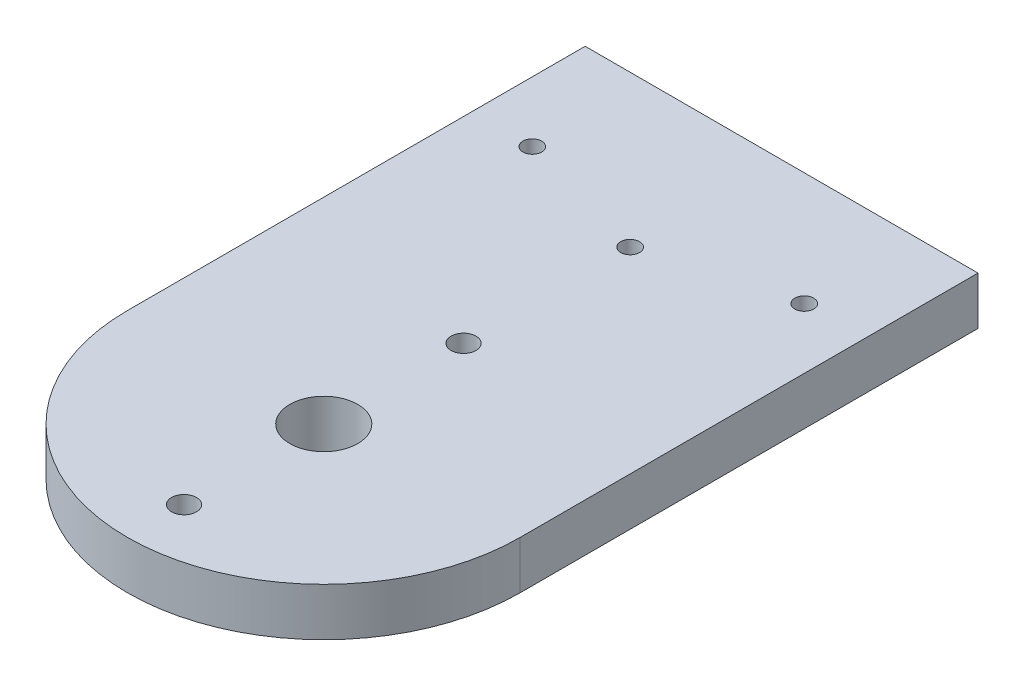
SolidWorks part; units mm, degrees
material "Aleación 6061"
ref_plane "Alzado" through (0, 0, 0) normal (0, 0, 1) x (1, 0, 0)
ref_plane "Planta" through (0, 0, 0) normal (0, 1, 0) x (1, 0, 0)
ref_plane "Vista lateral" through (0, 0, 0) normal (1, 0, 0) x (0, 0, -1)
sketch "Croquis1" plane through (0, 0, 0) normal (0, 1, 0) x (1, 0, 0)
  line L1 (126.4, -275.95) -> (178.4, -275.95)
  line L2 (126.4, -275.95) -> (126.4, -336.55)
  line L3 (126.4, -336.55) -> (178.4, -336.55)
  line L4 (178.4, -275.95) -> (178.4, -336.55)
  dimension "D1" = 126.4
  dimension "D2" = 275.95
  dimension "D3" = 178.4
  dimension "D4" = 275.95
  dimension "D5" = 126.4
  dimension "D6" = 336.55
  dimension "D7" = 178.4
  dimension "D8" = 336.55
extrude "Pared_B_chumacera_J5" add sketch "Croquis1" along normal blind 6.35 from offset 10.525
sketch "Croquis2" plane through (0, 0, 0) normal (0, 1, 0) x (1, 0, 0)
  circle A0 centre (152.4, -336.55) radius 26
  dimension "D1" = 52
  dimension "D2" = 152.4
  dimension "D3" = 336.55
extrude "Pared_B_chumacera_J5_redondeo" add sketch "Croquis2" along normal blind 6.35 from offset 10.525
sketch "Croquis3" plane through (0, 0, 0) normal (0, 1, 0) x (1, 0, 0)
  circle A0 centre (152.4, -336.55) radius 4.5
  circle A1 centre (152.4, -355.05) radius 1.65
  circle A2 centre (152.4, -318.05) radius 1.65
  dimension "D1" = 9
  dimension "D2" = 3.3
  dimension "D3" = 3.3
  dimension "D4" = 152.4
  dimension "D5" = 336.55
  dimension "D6" = 152.4
  dimension "D7" = 355.05
  dimension "D8" = 152.4
  dimension "D9" = 318.05
extrude "Paso_perno_y_rosca_M4_KFL08" cut sketch "Croquis3" along normal blind 6.35 from offset 10.525
sketch "Croquis4" plane through (0, 0, 0) normal (0, 1, 0) x (1, 0, 0)
  circle A0 centre (134.4, -290.95) radius 1.25
  circle A1 centre (170.4, -290.95) radius 1.25
  dimension "D1" = 2.5
  dimension "D2" = 2.5
  dimension "D3" = 134.4
  dimension "D4" = 290.95
  dimension "D5" = 170.4
  dimension "D6" = 290.95
extrude "Rosca_M3_escuadras" cut sketch "Croquis4" along normal blind 6.35 from offset 10.525
sketch "Croquis5" plane through (0, 0, 0) normal (0, 0, 1) x (1, 0, 0)
  circle A0 centre (130.4, -7.35) radius 2
  circle A1 centre (174.4, -7.35) radius 2
  dimension "D1" = 4
  dimension "D2" = 4
  dimension "D3" = 130.4
  dimension "D4" = 7.35
  dimension "D5" = 174.4
  dimension "D6" = 7.35
extrude "Pasadores_D4" cut sketch "Croquis5" along normal blind 8 from offset 275.95
sketch "Croquis6" plane through (0, 0, 0) normal (0, 1, 0) x (1, 0, 0)
  circle A0 centre (152.4, -296) radius 1.25
  dimension "D1" = 2.5
  dimension "D2" = 152.4
  dimension "D3" = 296
extrude "Rosca_M3_bases_cincho" cut sketch "Croquis6" along normal blind 6.35 from offset 10.525
